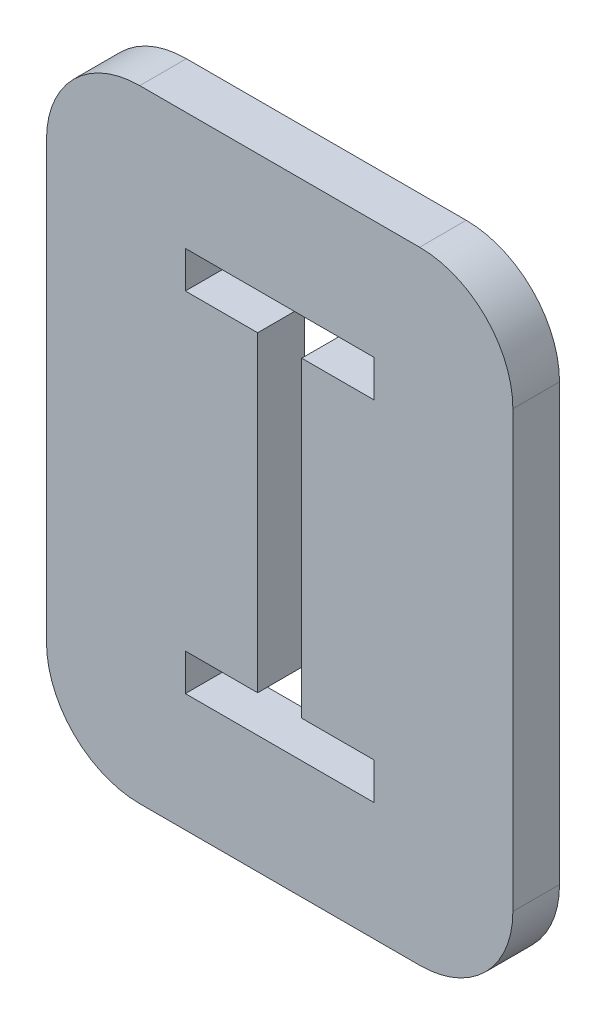
SolidWorks part; units mm, degrees
material "Custom Plastic"
ref_plane "Front Plane" through (0, 0, 0) normal (0, 0, 1) x (1, 0, 0)
ref_plane "Top Plane" through (0, 0, 0) normal (0, 1, 0) x (1, 0, 0)
ref_plane "Right Plane" through (0, 0, 0) normal (1, 0, 0) x (0, 0, -1)
sketch "Sketch1" plane through (0, 0, 0) normal (0, 0, 1) x (1, 0, 0)
  line L0 (-3.8528, -6.3673) -> (-3.8528, -7.874)
  line L1 (3.8527, -6.3673) -> (3.8527, -7.874)
  line L23 (-5.715, 12.7) -> (5.715, 12.7)
  line L24 (-9.525, 8.89) -> (-9.525, -8.89)
  line L25 (-5.715, -12.7) -> (5.715, -12.7)
  line L26 (9.525, 8.89) -> (9.525, -8.89)
  line L27 (-9.525, 12.7) -> (9.525, -12.7) construction
  line L28 (-9.525, -12.7) -> (9.525, 12.7) construction
  line L29 (-3.8528, 7.874) -> (3.8527, 7.874)
  line L30 (-3.8528, 7.874) -> (-3.8528, 6.3673)
  line L31 (-3.8528, -7.874) -> (3.8527, -7.874)
  line L32 (3.8527, 7.874) -> (3.8527, 6.3673)
  line L33 (-3.8528, 7.874) -> (3.8527, -7.874) construction
  line L34 (-3.8528, -7.874) -> (3.8527, 7.874) construction
  line L35 (-3.8528, 6.3673) -> (-0.9, 6.3673)
  line L37 (-3.8528, -6.3673) -> (-0.9, -6.3673)
  line L38 (-0.9, 6.3673) -> (-0.9, -6.3673)
  line L39 (3.8527, 6.3673) -> (0.9, 6.3673)
  line L41 (3.8527, -6.3673) -> (0.9, -6.3673)
  line L42 (0.9, 6.3673) -> (0.9, -6.3673)
  arc A0 (-5.715, -12.7) -> (-9.525, -8.89) centre (-5.715, -8.89) cw
  arc A1 (5.715, -12.7) -> (9.525, -8.89) centre (5.715, -8.89) ccw
  arc A2 (9.525, 8.89) -> (5.715, 12.7) centre (5.715, 8.89) ccw
  arc A3 (-9.525, 8.89) -> (-5.715, 12.7) centre (-5.715, 8.89) cw
  point P0 (0, 0)
  point P5 (0, 0)
  point P32 (0, 0)
  dimension "D8" = 3.81
  dimension "D2" = 12.7346
  dimension "D3" = 19.05
  dimension "D4" = 25.4
  dimension "D5" = 1.8
  dimension "D6" = 2.9527
  dimension "D7" = 2.9528
  dimension "D14" = 1.5067
  dimension "D15" = 1.5067
extrude "Boss-Extrude1" add sketch "Sketch1" along normal mid plane 1.905
